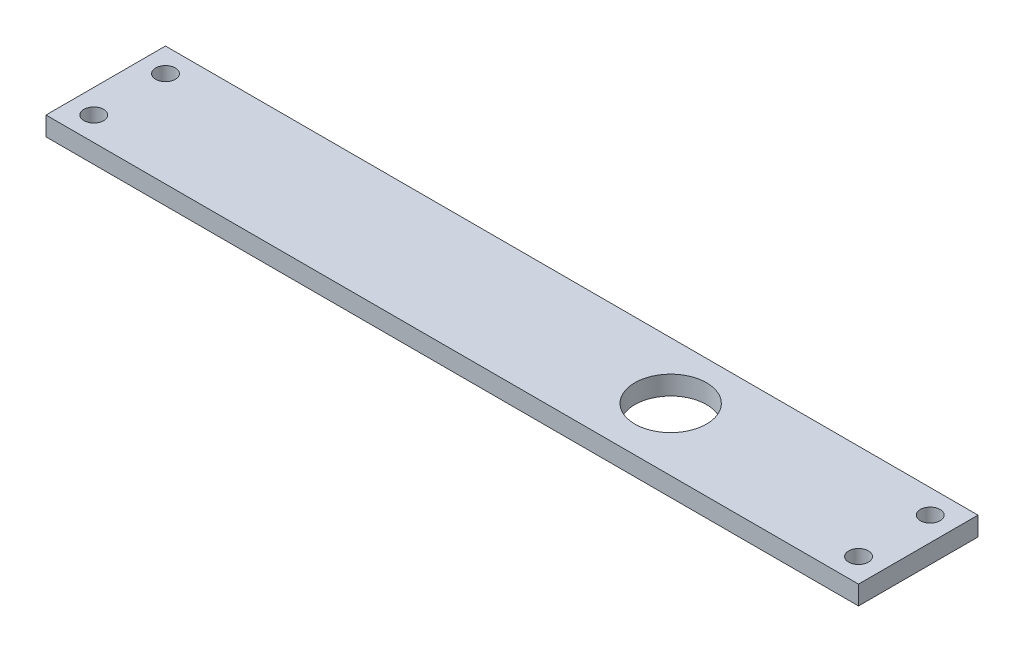
SolidWorks part; units mm, degrees
ref_plane "Front" through (0, 0, 0) normal (0, 0, 1) x (1, 0, 0)
ref_plane "Top" through (0, 0, 0) normal (0, 1, 0) x (1, 0, 0)
ref_plane "Right" through (0, 0, 0) normal (1, 0, 0) x (0, 0, -1)
sketch "Sketch1" plane through (0, 0, 0) normal (0, 1, 0) x (1, 0, 0)
  line L1 (0, 0) -> (136, 0)
  line L2 (0, 0) -> (0, -20)
  line L3 (0, -20) -> (136, -20)
  line L4 (136, 0) -> (136, -20)
  circle A0 centre (4, -4) radius 1.65
  circle A1 centre (132, -4) radius 1.65
  circle A3 centre (94.0855, -9.5242) radius 6
  circle A4 centre (4, -16) radius 1.65
  circle A5 centre (132, -16) radius 1.65
  dimension "D2" = 4
  dimension "D3" = 4
  dimension "D6" = 4
  dimension "D9" = 12
  dimension "D10" = 12
  dimension "D1" = 136
  dimension "D4" = 20
  dimension "D5" = 5.5242
  dimension "D7" = 4
  dimension "D8" = 37.9145
extrude "Boss-Extrude1" add sketch "Sketch1" along normal blind 3.175
